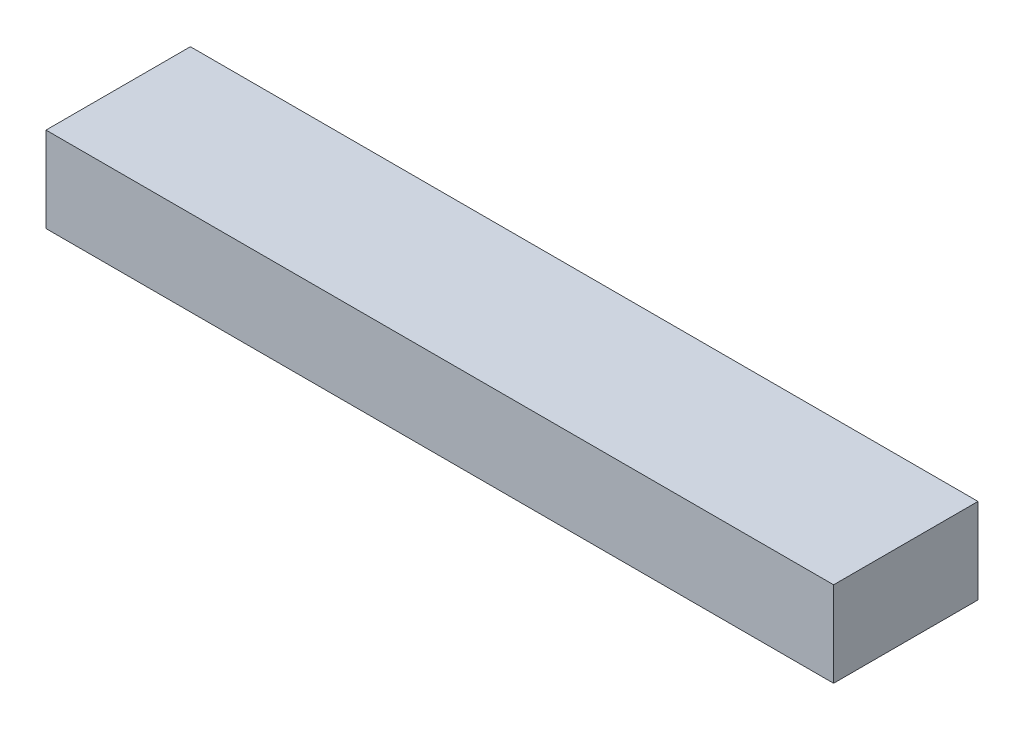
SolidWorks part; units mm, degrees
ref_plane "前视基准面" through (0, 0, 0) normal (0, 0, 1) x (1, 0, 0)
ref_plane "上视基准面" through (0, 0, 0) normal (0, 1, 0) x (1, 0, 0)
ref_plane "右视基准面" through (0, 0, 0) normal (1, 0, 0) x (0, 0, -1)
sketch "草图1" plane through (0, 0, 0) normal (0, 1, 0) x (1, 0, 0)
  line L1 (-58.0825, 33.1134) -> (61.9175, 33.1134)
  line L2 (-58.0825, 33.1134) -> (-58.0825, 11.1134)
  line L3 (-58.0825, 11.1134) -> (61.9175, 11.1134)
  line L4 (61.9175, 33.1134) -> (61.9175, 11.1134)
  circle A0 centre (-53.0825, 29.6134) radius 2
  circle A1 centre (56.9175, 29.6134) radius 2
  point P8 (0, 0)
  point P10 (58.8436, 29.5222)
  dimension "D5" = 4
  dimension "D8" = 4
  dimension "D1" = 22
  dimension "D2" = 120
  dimension "D3" = 5
  dimension "D4" = 3.5
  dimension "D6" = 3.5
  dimension "D7" = 5
extrude "凸台-拉伸1" add sketch "草图1" along normal blind 13 contours L1 L4 L3 L2
